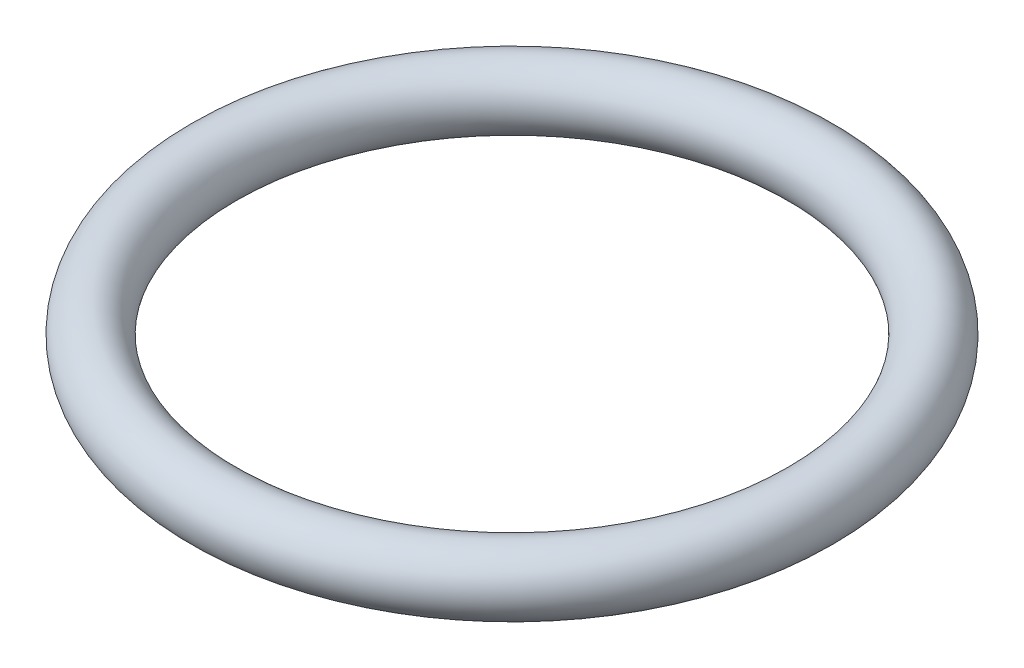
SolidWorks part; units mm, degrees
ref_plane "Спереди" through (0, 0, 0) normal (0, 0, 1) x (1, 0, 0)
ref_plane "Сверху" through (0, 0, 0) normal (0, 1, 0) x (1, 0, 0)
ref_plane "Справа" through (0, 0, 0) normal (1, 0, 0) x (0, 0, -1)
sketch "Ske" plane through (0, 0, 0) normal (0, 0, 1) x (1, 0, 0)
  line L0 (0, 9.41) -> (0, 0) construction
  circle A0 centre (27.4, 0) radius 2.9
  dimension "D1" = 49
  dimension "D" = 5.8
revolve "Основание-Повернуть" add sketch "Ske" angle 360 about L0
sketch "Эскиз2" plane through (0, 0, 0) normal (0, 1, 0) x (1, 0, 0)
  circle A0 centre (0, 0) radius 7.6706
surface "Поверхность-Вытянуть1" sketch "Эскиз2" parameters "D1"=3
sketch "Эскиз3" plane through (0, 0, 0) normal (0, 0, 1) x (1, 0, 0)
  line L0 (0, -2.9) -> (27.4, -2.9)
  line L1 (0, 2.9362) -> (0, -2.5308) construction
  line L2 (0, 9.41) -> (0, 0) construction
  line L3 (0, 0) -> (0, 3) construction
  circle A1 centre (27.4, 0) radius 2.9 construction
surface "Поверхность-Повернуть1" sketch "Эскиз3" parameters "D1"=360
